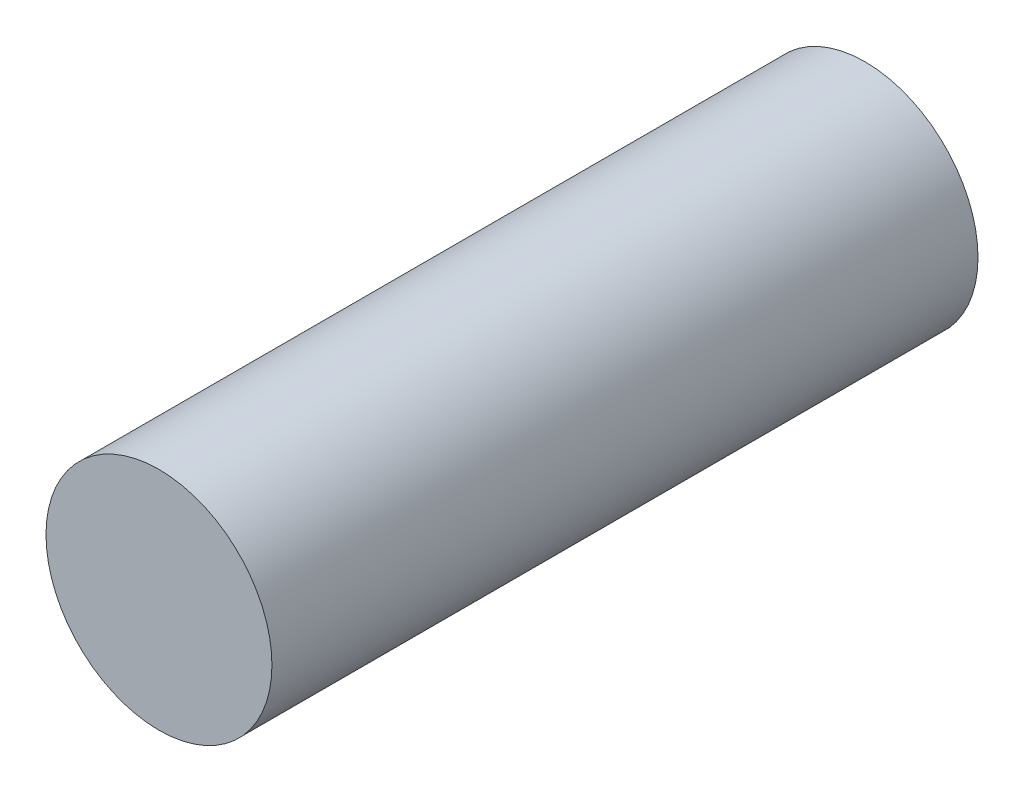
SolidWorks part; units mm, degrees
ref_plane "前视基准面" through (0, 0, 0) normal (0, 0, 1) x (1, 0, 0)
ref_plane "上视基准面" through (0, 0, 0) normal (0, 1, 0) x (1, 0, 0)
ref_plane "右视基准面" through (0, 0, 0) normal (1, 0, 0) x (0, 0, -1)
other "Configuration Table"
sketch "草图1" plane through (0, 0, 0) normal (0, 0, 1) x (1, 0, 0)
  circle A0 centre (0, 0) radius 4
  dimension "D1" = 8
extrude "凸台-拉伸1" add sketch "草图1" along normal blind 25
